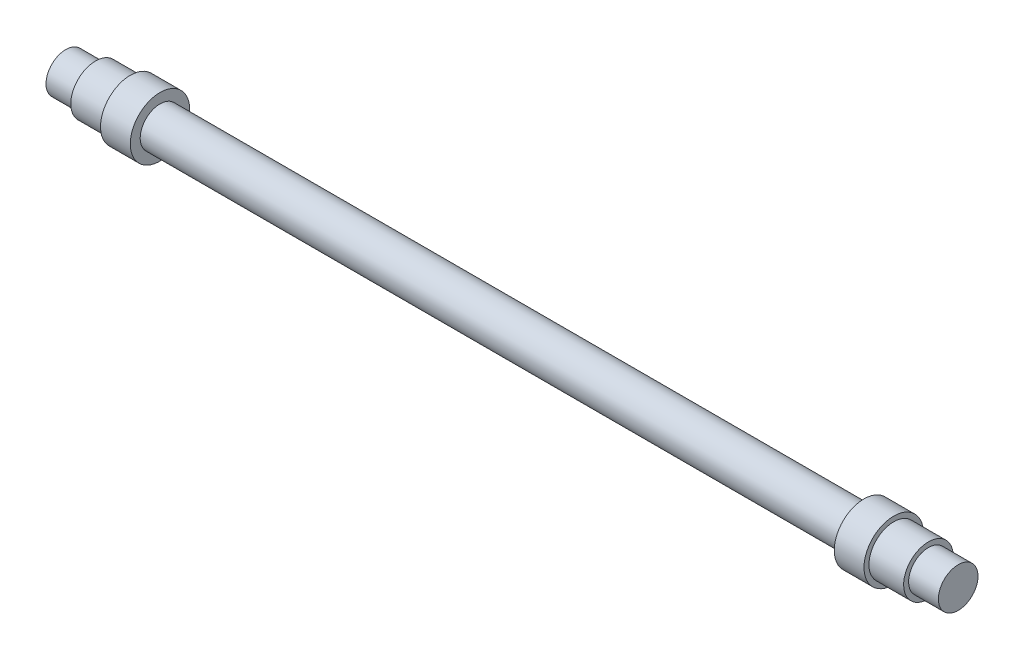
SolidWorks part; units mm, degrees
material "Brass"
ref_plane "Front Plane" through (0, 0, 0) normal (0, 0, 1) x (1, 0, 0)
ref_plane "Top Plane" through (0, 0, 0) normal (0, 1, 0) x (1, 0, 0)
ref_plane "Right Plane" through (0, 0, 0) normal (1, 0, 0) x (0, 0, -1)
sketch "Sketch1" plane through (0, 0, 0) normal (0, 0, 1) x (1, 0, 0)
  line L0 (0, 0) -> (0, 2)
  line L1 (0, 2) -> (3, 2)
  line L2 (3, 2) -> (3, 2.5)
  line L3 (6.5, 3) -> (9.5, 3)
  line L4 (9.5, 3) -> (9.5, 2)
  line L5 (3, 2.5) -> (6.5, 2.5)
  line L6 (6.5, 2.5) -> (6.5, 3)
  line L7 (9.5, 2) -> (80.5, 2)
  line L8 (83.5, 3) -> (83.5, 2.5)
  line L9 (83.5, 2.5) -> (87, 2.5)
  line L10 (87, 2.5) -> (87, 2)
  line L11 (80.5, 2) -> (80.5, 3)
  line L12 (80.5, 3) -> (83.5, 3)
  line L13 (87, 2) -> (90, 2)
  line L14 (90, 2) -> (90, 0)
  line L15 (90, 0) -> (0, 0)
  dimension "D1" = 2
  dimension "D2" = 3
  dimension "D3" = 3.5
  dimension "D4" = 3
  dimension "D5" = 2.5
  dimension "D6" = 3
  dimension "D7" = 90
  dimension "D8" = 2
revolve "Revolve1" add sketch "Sketch1" angle 360 about L15
